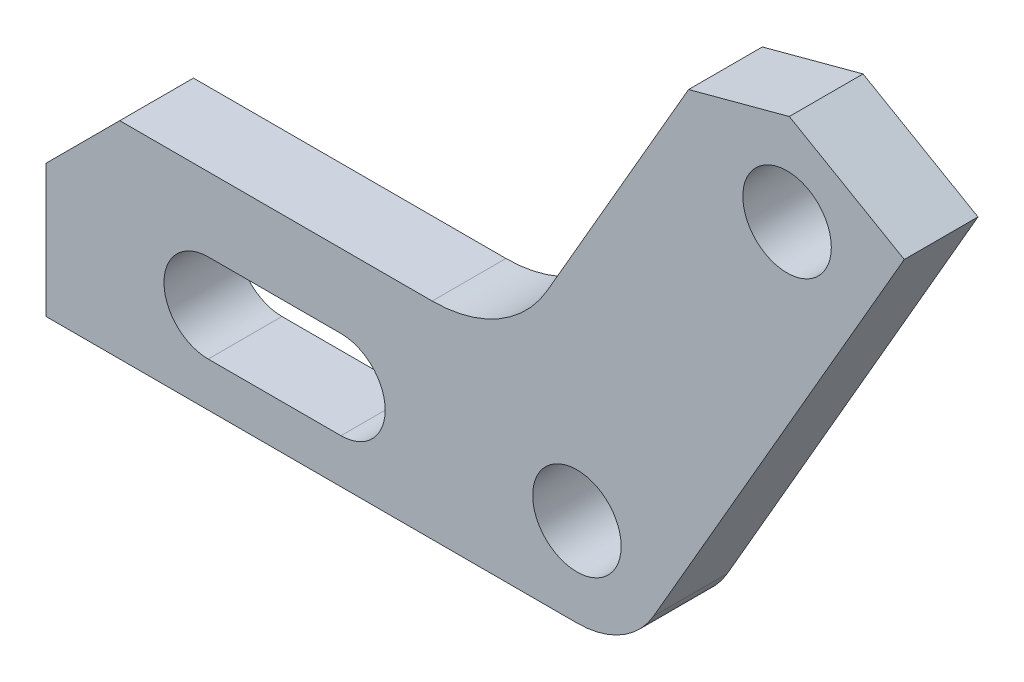
SolidWorks part; units mm, degrees
ref_plane "Alzado" through (0, 0, 0) normal (0, 0, 1) x (1, 0, 0)
ref_plane "Planta" through (0, 0, 0) normal (0, 1, 0) x (1, 0, 0)
ref_plane "Vista lateral" through (0, 0, 0) normal (1, 0, 0) x (0, 0, -1)
sketch "Croquis1" plane through (0, 0, 0) normal (0, 0, 1) x (1, 0, 0)
  line L0 (-32, 0) -> (0, 0) construction
  line L1 (0, 0) -> (28.5, 49.3634) construction
  line L2 (-62, 16) -> (-19.6299, 16)
  line L3 (-4.0415, 25) -> (15.1436, 58.2295)
  line L4 (28.8038, 61.8897) -> (44.3923, 52.8897)
  line L5 (44.3923, 52.8897) -> (10.3923, -6)
  line L6 (0, -12) -> (-72, -12)
  line L7 (-72, -12) -> (-72, 6)
  line L8 (-72, 6) -> (-62, 16)
  line L9 (15.1436, 58.2295) -> (28.8038, 61.8897)
  line L10 (-32, 0) -> (-50, 0) construction
  line L11 (-32, -6) -> (-50, -6)
  line L12 (-32, 6) -> (-50, 6)
  circle A0 centre (0, 0) radius 6
  circle A1 centre (28.5, 49.3634) radius 6
  arc A2 (-32, -6) -> (-32, 6) centre (-32, 0) ccw
  arc A3 (-50, 6) -> (-50, -6) centre (-50, 0) ccw
  arc A4 (-19.6299, 16) -> (-4.0415, 25) centre (-19.6299, 34) ccw
  arc A5 (10.3923, -6) -> (0, -12) centre (0, 0) cw
  point P3 (-72, 16)
  point P7 (20.1436, 66.8897)
  point P16 (-41, 0)
  dimension "D8" = 12
  dimension "D16" = 6
  dimension "D17" = 18
  dimension "D18" = 12
  dimension "D1" = 12
  dimension "D2" = 12
  dimension "D3" = 28
  dimension "D4" = 28
  dimension "D5" = 120
  dimension "D6" = 72
  dimension "D7" = 68
  dimension "D9" = 57
  dimension "D10" = 10
  dimension "D11" = 45
  dimension "D12" = 10
  dimension "D13" = 45
  dimension "D14" = 32
  dimension "D15" = 50
extrude "Saliente-Extruir1" add sketch "Croquis1" along normal blind 10
